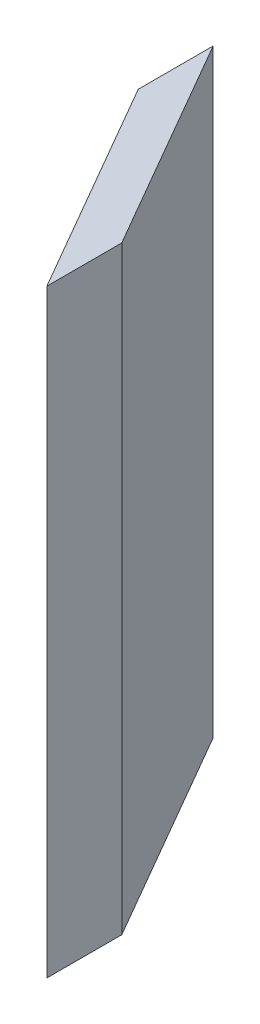
SolidWorks part; units mm, degrees
ref_plane "前视基准面" through (0, 0, 0) normal (0, 0, 1) x (1, 0, 0)
ref_plane "上视基准面" through (0, 0, 0) normal (0, 1, 0) x (1, 0, 0)
ref_plane "右视基准面" through (0, 0, 0) normal (1, 0, 0) x (0, 0, -1)
sketch "草图1" plane through (0, 0, 0) normal (0, 1, 0) x (1, 0, 0)
  line L0 (0, 0) -> (0, -15)
  line L1 (0, -15) -> (25, -58.3013)
  line L2 (25, -58.3013) -> (25, -43.3013)
  line L3 (25, -43.3013) -> (0, 0)
extrude "凸台-拉伸1" add sketch "草图1" along normal blind 120
